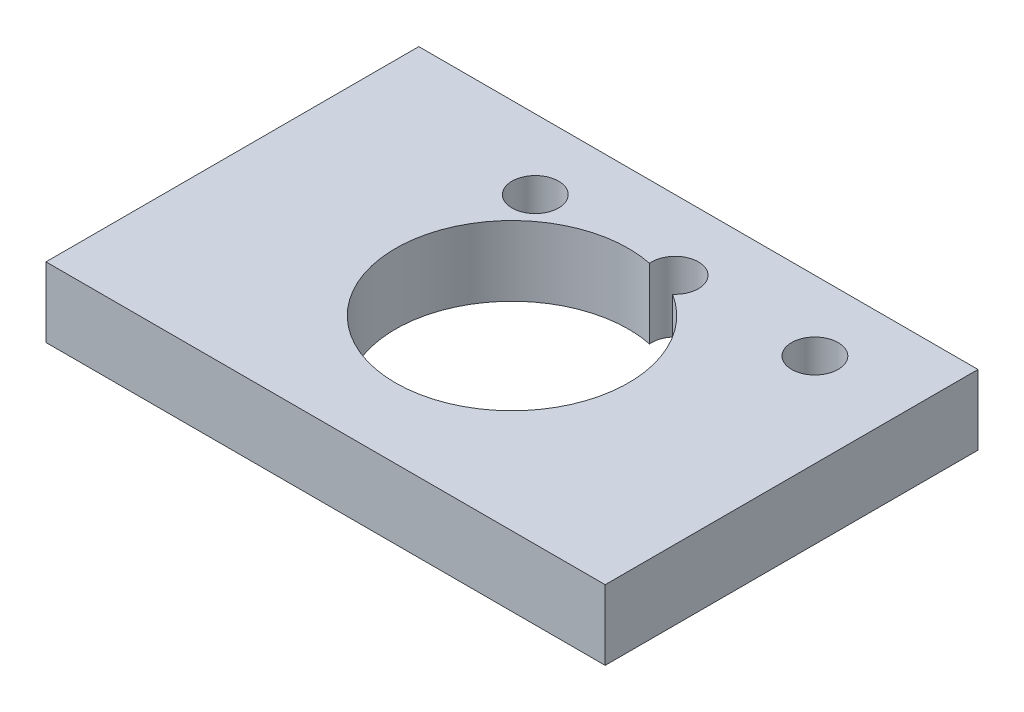
SolidWorks part; units mm, degrees
ref_plane "前视基准面" through (0, 0, 0) normal (0, 0, 1) x (1, 0, 0)
ref_plane "上视基准面" through (0, 0, 0) normal (0, 1, 0) x (1, 0, 0)
ref_plane "右视基准面" through (0, 0, 0) normal (1, 0, 0) x (0, 0, -1)
other "Configuration Table"
sketch "草图1" plane through (0, 0, 0) normal (0, 1, 0) x (1, 0, 0)
  line L1 (-60, -40) -> (60, -40)
  line L2 (-60, -40) -> (-60, 40)
  line L3 (-60, 40) -> (60, 40)
  line L4 (60, -40) -> (60, 40)
extrude "凸台-拉伸1" add sketch "草图1" along normal blind 15
sketch "草图2" plane through (0, 0, 0) normal (0, 1, 0) x (1, 0, 0)
  circle A0 centre (0, 0) radius 25
extrude "切除-拉伸1" cut sketch "草图2" along normal blind 15
sketch "草图3" plane through (0, 0, 0) normal (0, 1, 0) x (1, 0, 0)
  circle A0 centre (40, 25) radius 5
extrude "切除-拉伸2" cut sketch "草图3" along normal blind 15
pattern_linear "阵列(线性)1" count 3 spacing 30 along (-1, 0, 0) of "切除-拉伸2"
